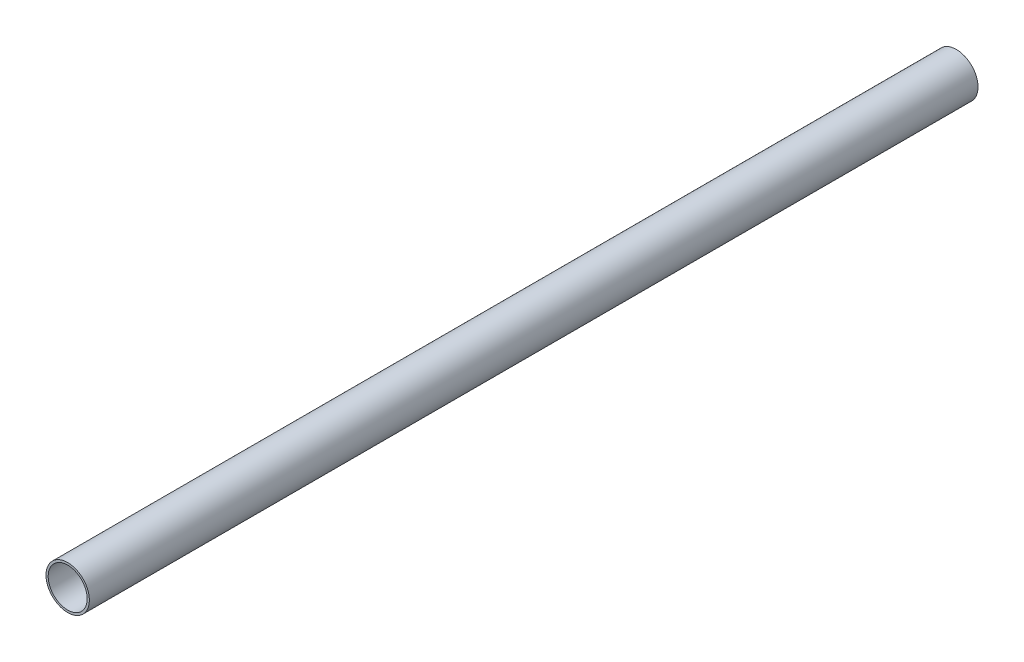
SolidWorks part; units mm, degrees
ref_plane "Front Plane" through (0, 0, 0) normal (0, 0, 1) x (1, 0, 0)
ref_plane "Top Plane" through (0, 0, 0) normal (0, 1, 0) x (1, 0, 0)
ref_plane "Right Plane" through (0, 0, 0) normal (1, 0, 0) x (0, 0, -1)
sketch "Sketch2" plane through (0, 0, 0) normal (0, 0, 1) x (1, 0, 0)
  circle A0 centre (0, 0) radius 10
  circle A1 centre (0, 0) radius 9
extrude "Boss-Extrude1" add sketch "Sketch2" along normal blind 410
